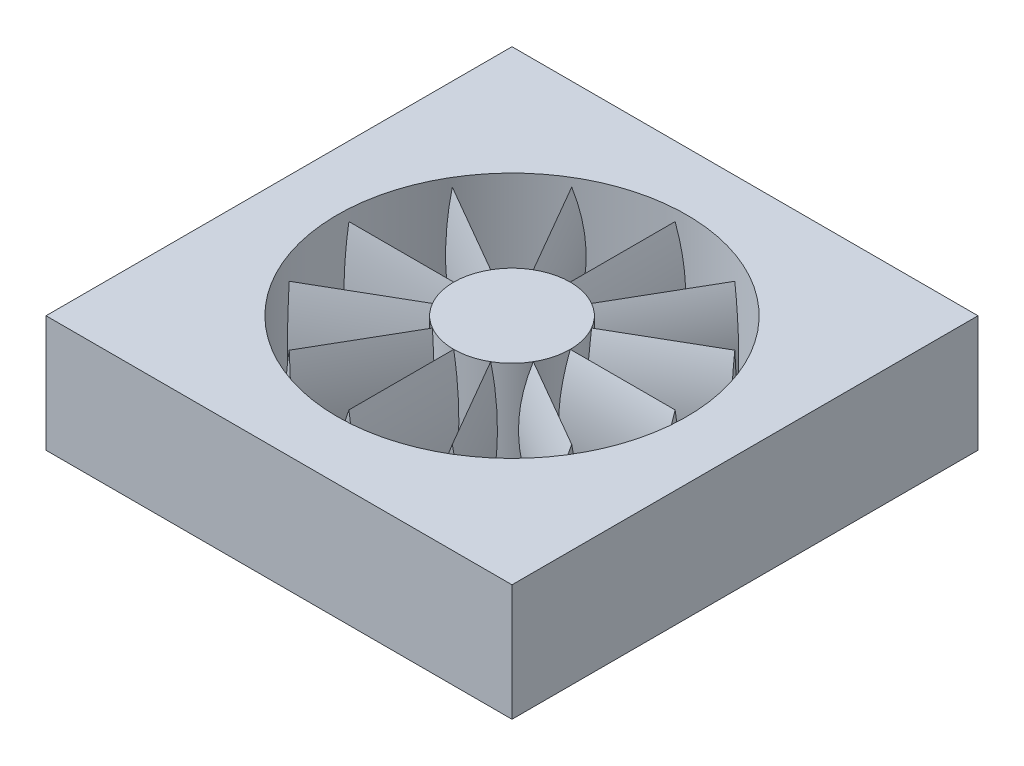
SolidWorks part; units mm, degrees
ref_plane "前视基准面" through (0, 0, 0) normal (0, 0, 1) x (1, 0, 0)
ref_plane "上视基准面" through (0, 0, 0) normal (0, 1, 0) x (1, 0, 0)
ref_plane "右视基准面" through (0, 0, 0) normal (1, 0, 0) x (0, 0, -1)
sketch "草图1" plane through (0, 0, 0) normal (0, 1, 0) x (1, 0, 0)
  line L1 (-14.349, 12.687) -> (25.651, 12.687)
  line L2 (-14.349, 12.687) -> (-14.349, -27.313)
  line L3 (-14.349, -27.313) -> (25.651, -27.313)
  line L4 (25.651, 12.687) -> (25.651, -27.313)
  line L5 (-14.349, 12.687) -> (25.651, -27.313) construction
  line L6 (-14.349, -27.313) -> (25.651, 12.687) construction
  circle A0 centre (5.651, -7.313) radius 15
  circle A1 centre (5.651, -7.313) radius 5
  point P4 (5.651, -7.313)
  dimension "D3" = 30
  dimension "D4" = 10
  dimension "D1" = 40
  dimension "D2" = 40
extrude "凸台-拉伸1" add sketch "草图1" along normal blind 10 contours L4 L1 L2 L3 A0 | A1
ref_plane "基准面1" through (5.651, 0, 0) normal (-1, 0, 0) x (0, 0, 1)
sketch "草图2" plane through (5.651, 0, 0) normal (-1, 0, 0) x (0, 0, 1)
  line L0 (-12.687, 10) -> (27.313, 10) construction
  line L1 (-12.687, 0) -> (27.313, 0) construction
  arc A0 (7.313, 10) -> (7.313, 0) centre (20.5951, 5) ccw
  arc A1 (7.313, 10) -> (7.313, 0) centre (-22.2055, 5) cw
extrude "凸台-拉伸2" add sketch "草图2" along normal blind 14
pattern_circular "阵列(圆周)1" count 12 every 30 about axis through (5.651, 0, 7.313) along (0, 1, 0) of "凸台-拉伸2"
